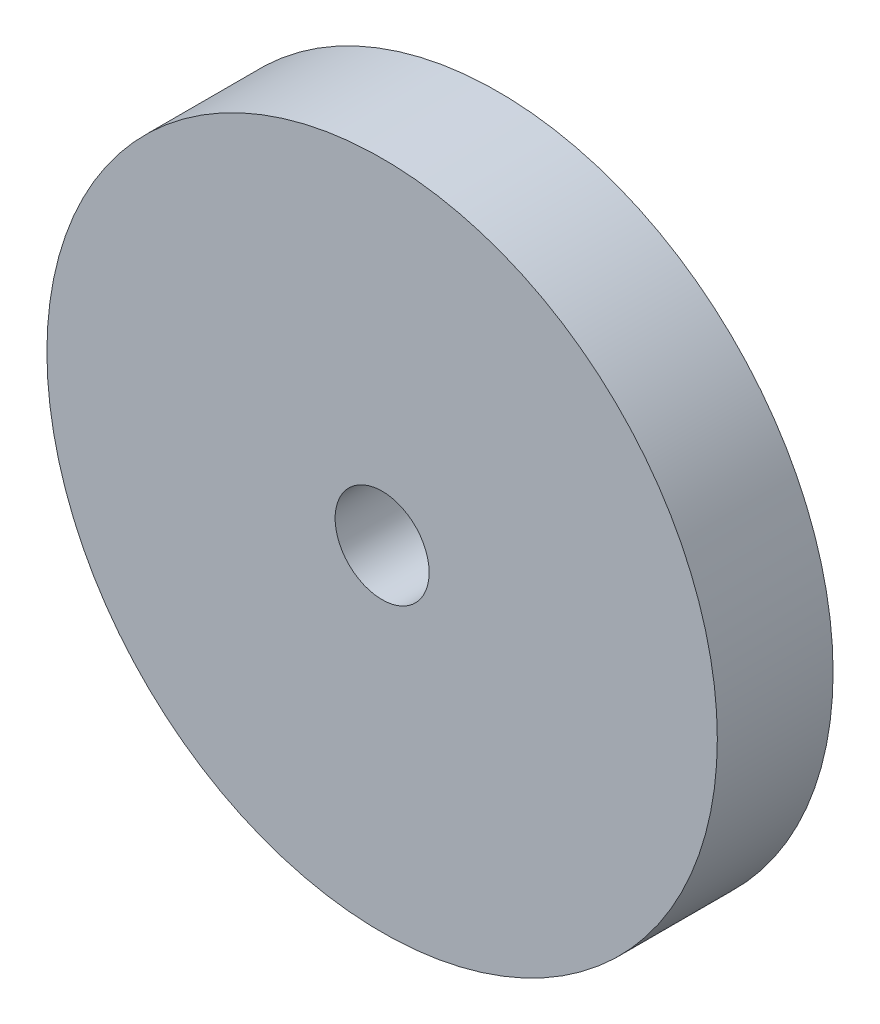
SolidWorks part; units mm, degrees
ref_plane "Front Plane" through (0, 0, 0) normal (0, 0, 1) x (1, 0, 0)
ref_plane "Top Plane" through (0, 0, 0) normal (0, 1, 0) x (1, 0, 0)
ref_plane "Right Plane" through (0, 0, 0) normal (1, 0, 0) x (0, 0, -1)
sketch "Sketch1" plane through (0, 0, 0) normal (0, 0, 1) x (1, 0, 0)
  circle A0 centre (0, 0) radius 17.3736
  circle A1 centre (0, 0) radius 2.4365
  dimension "D1" = 34.7472
  dimension "D2" = 4.873
extrude "Boss-Extrude1" add sketch "Sketch1" along normal blind 6
